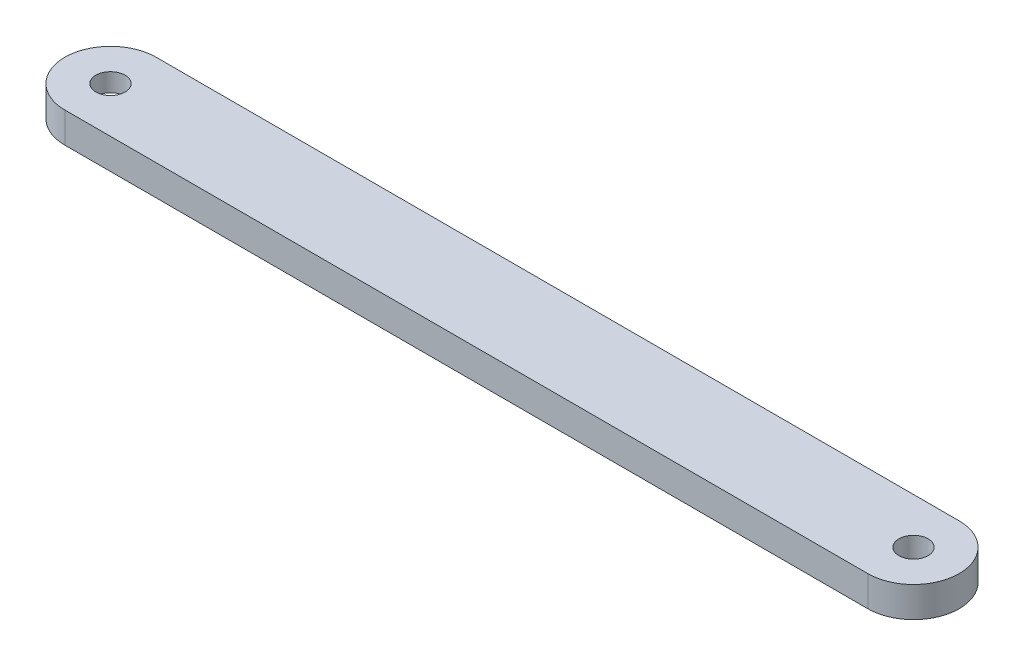
SolidWorks part; units mm, degrees
ref_plane "Front Plane" through (0, 0, 0) normal (0, 0, 1) x (1, 0, 0)
ref_plane "Top Plane" through (0, 0, 0) normal (0, 1, 0) x (1, 0, 0)
ref_plane "Right Plane" through (0, 0, 0) normal (1, 0, 0) x (0, 0, -1)
sketch "Sketch1" plane through (0, 0, 0) normal (0, 1, 0) x (1, 0, 0)
  line L0 (-181.8458, 0) -> (181.8458, 0) construction
  line L1 (-181.8458, 7.5) -> (-50, 7.5)
  line L2 (-181.8458, -7.5) -> (-50, -7.5)
  line L3 (0, 133.0135) -> (0, -120.6232) construction
  line L4 (-50, 63.0571) -> (-50, -63.0571) construction
  line L5 (50, 63.0571) -> (50, -63.0571) construction
  arc A0 (-181.8458, 7.5) -> (-181.8458, -7.5) centre (-181.8458, 0) ccw
  circle A2 centre (-181.8458, 0) radius 2.4
  arc A4 (-50, -7.5) -> (-50, 7.5) centre (-50, 0) ccw
  circle A6 centre (-50, 0) radius 2.4
  point P3 (0, 0)
  dimension "D3" = 100
  dimension "D1" = 363.6916
  dimension "D2" = 15
  dimension "D4" = 50
extrude "Boss-Extrude1" add sketch "Sketch1" along normal blind 5
sketch "Sketch2" plane through (0, 0, 0) normal (0, -1, 0) x (1, 0, 0)
  circle A0 centre (-181.8458, 0) radius 5.9
extrude "Cut-Extrude1" cut sketch "Sketch2" against normal blind 2
scale "Scale1" scale about centroid uniform scaling yes scale factor 0.8
